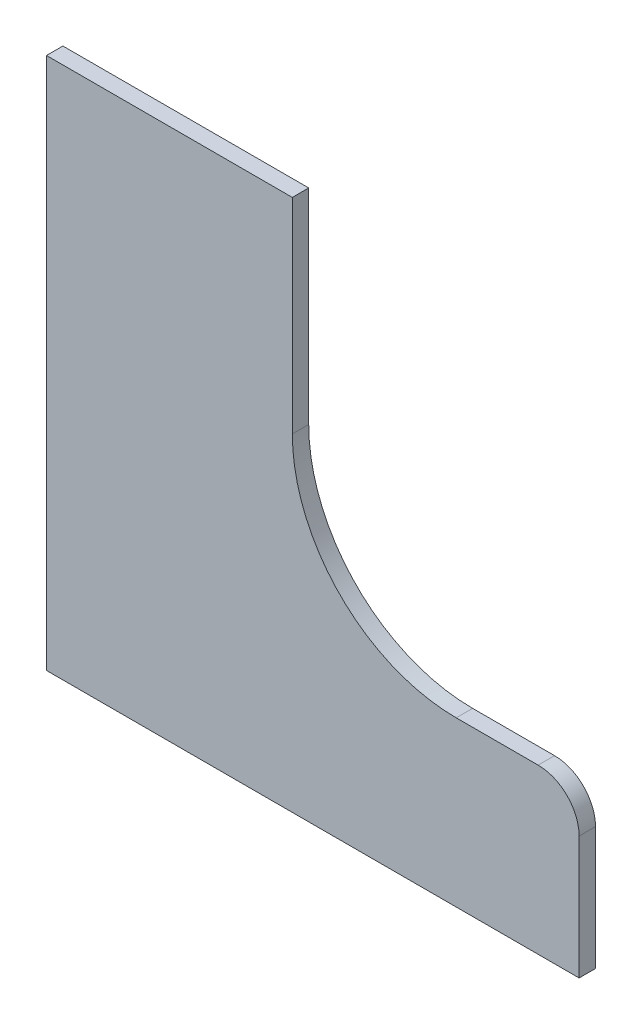
SolidWorks part; units mm, degrees
ref_plane "Front Plane" through (0, 0, 0) normal (0, 0, 1) x (1, 0, 0)
ref_plane "Top Plane" through (0, 0, 0) normal (0, 1, 0) x (1, 0, 0)
ref_plane "Right Plane" through (0, 0, 0) normal (1, 0, 0) x (0, 0, -1)
sketch "Sketch1" plane through (0, 0, 0) normal (0, 0, 1) x (1, 0, 0)
  line L6 (-482.6667, 166) -> (-182.6667, 166)
  line L9 (167.3333, -284) -> (167.3333, -484)
  line L11 (-482.6667, -484) -> (167.3333, -484)
  line L12 (-482.6667, 166) -> (-482.6667, -484)
  line L13 (-182.6667, 166) -> (-182.6667, -84)
  line L14 (17.3333, -284) -> (167.3333, -284)
  arc A2 (17.3333, -284) -> (-182.6667, -84) centre (17.3333, -84) cw
  dimension "D3" = 200
  dimension "D1" = 200
  dimension "D2" = 300
  dimension "D4" = 650
  dimension "D5" = 650
extrude "Boss-Extrude1" add sketch "Sketch1" along normal blind 20
fillet "Fillet1" radius 50 1 edges at (167.3333, -284, 10)
